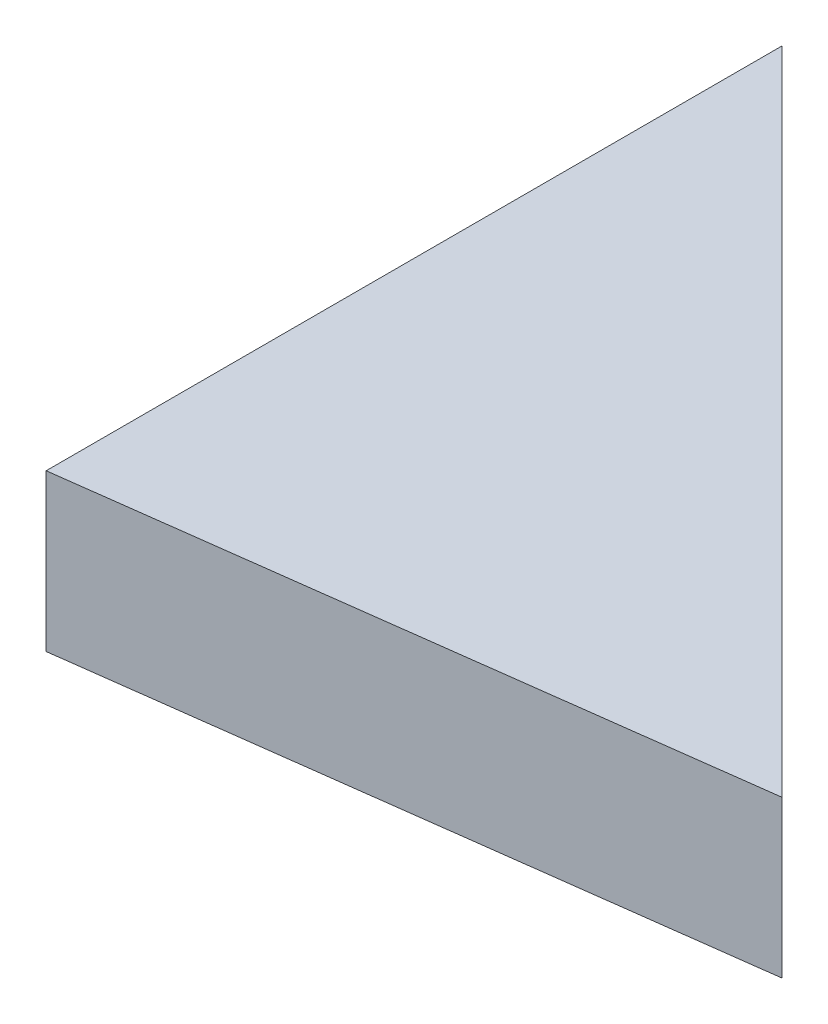
SolidWorks part; units mm, degrees
ref_plane "Front Plane" through (0, 0, 0) normal (0, 0, 1) x (1, 0, 0)
ref_plane "Top Plane" through (0, 0, 0) normal (0, 1, 0) x (1, 0, 0)
ref_plane "Right Plane" through (0, 0, 0) normal (1, 0, 0) x (0, 0, -1)
sketch "Sketch1" plane through (0, 0, 0) normal (0, 1, 0) x (1, 0, 0)
  line L0 (0, 0) -> (-30.4819, 0)
  line L1 (0, -16.6023) -> (0, 16.6023)
  line L2 (0, -13.4273) -> (-20.7175, -13.4273)
  line L3 (-20.7175, -13.4273) -> (-20.7175, -16.6023)
  line L4 (-20.7175, -16.6023) -> (0, -16.6023)
  circle A0 centre (0, 0) radius 9.1512
  circle A1 centre (-30.4819, 0) radius 16.6023
  circle A2 centre (0, 0) radius 16.6023
  point P8 (0, -13.4273)
  dimension "D1" = 3.175
sketch "Sketch2" plane through (0, 0, 0) normal (0, 1, 0) x (1, 0, 0)
  line L0 (-19.6331, 9.1492) -> (-19.6331, -11.5682)
  line L1 (52.4038, -8.6543) -> (52.4038, -23.5712)
  line L2 (52.4038, -8.6543) -> (65.5947, -21.8451)
  line L3 (52.4038, -23.5712) -> (65.5947, -21.8451)
  dimension "D1" = 45
  dimension "D2" = 82.545
extrude "Boss-Extrude1" add sketch "Sketch2" along normal blind 3.175 contours L1 L3 L2
